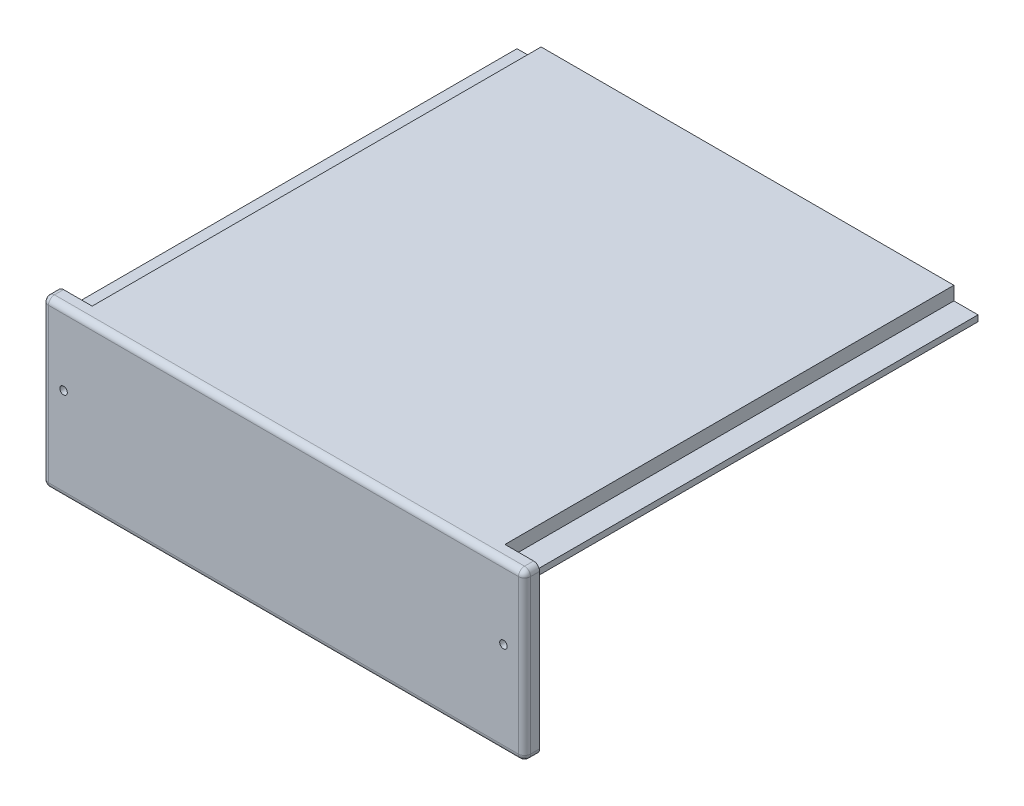
SolidWorks part; units mm, degrees
ref_plane "Front Plane" through (0, 0, 0) normal (0, 0, 1) x (1, 0, 0)
ref_plane "Top Plane" through (0, 0, 0) normal (0, 1, 0) x (1, 0, 0)
ref_plane "Right Plane" through (0, 0, 0) normal (1, 0, 0) x (0, 0, -1)
sketch "Sketch1" plane through (0, 0, 0) normal (0, 0, 1) x (1, 0, 0)
  line L0 (78, 0) -> (-78, 0) construction
  line L1 (80, 55) -> (-80, 55)
  line L2 (80, 55) -> (80, 0)
  line L3 (80, 0) -> (-80, 0)
  line L4 (-80, 55) -> (-80, 0)
  line L5 (-80, 2) -> (-80, 53) construction
  line L6 (-69, 55) -> (69, 55) construction
  line L7 (80, 2) -> (80, 53) construction
extrude "Boss-Extrude1" add sketch "Sketch1" along normal blind 5
sketch "Sketch4" plane through (0, 0, 0) normal (0, 0, -1) x (-1, 0, 0)
  line L1 (-69, 17) -> (69, 17)
  line L2 (-69, 17) -> (-69, 13)
  line L3 (-69, 13) -> (69, 13)
  line L4 (69, 17) -> (69, 13)
  line L5 (-69, 10) -> (69, 10)
  line L6 (-69, 10) -> (-69, 6)
  line L7 (-69, 6) -> (69, 6)
  line L8 (69, 10) -> (69, 6)
  line L12 (77, 10) -> (-77, 10) construction
  line L13 (77, 6) -> (-77, 6) construction
  line L14 (-77, 17) -> (77, 17) construction
  dimension "D1" = 4
extrude "Boss-Extrude3" add sketch "Sketch4" along normal blind 4
fillet "Fillet1" radius 2 8 edges at (80, 27.5, 5) (-80, 27.5, 5) (80, 0, 2.5) (0, 0, 5) (-80, 0, 2.5) (0, 55, 5) (80, 55, 2.5) (-80, 55, 2.5)
sketch "Sketch10" plane through (0, 0, 0) normal (0, 0, -1) x (-1, 0, 0)
  circle A1 centre (-73, 31) radius 1.25
  dimension "D1" = 2.5
extrude "Cut-Extrude1" cut sketch "Sketch10" against normal up to next
mirror "Mirror1" about plane through (0, 0, 0) normal (1, 0, 0) of "Cut-Extrude1"
sketch "Sketch13" plane through (0, 0, 0) normal (0, 0, -1) x (-1, 0, 0)
  line L0 (-68.5, 55) -> (-68.5, 50.5)
  line L1 (-80, 55) -> (80, 55) construction
  line L2 (-69, 55) -> (-69, 51) construction
  line L3 (-68.5, 50.5) -> (-76.5, 50.5)
  line L4 (-76.5, 50.5) -> (-76.5, 48.5)
  line L5 (-76.5, 48.5) -> (-68.5, 48.5)
  line L6 (-68.5, 48.5) -> (-68.5, 45)
  line L7 (-68.5, 45) -> (68.5, 45)
  line L9 (0, 45) -> (0, 55) construction
  line L10 (68.5, 55) -> (-68.5, 55)
  line L12 (76.5, 50.5) -> (76.5, 51) construction
  line L14 (76.5, 48.5) -> (76.5, 48) construction
  line L15 (-77, 51) -> (-77, 48) construction
  line L16 (-76.5, 48.5) -> (-76.5, 48) construction
  line L18 (-76.5, 50.5) -> (-76.5, 51) construction
  line L19 (-69, 51) -> (-77, 51) construction
  line L20 (-69, 45) -> (-68.5, 45) construction
  line L21 (68.5, 48.5) -> (68.5, 45)
  line L22 (76.5, 48.5) -> (68.5, 48.5)
  line L23 (76.5, 50.5) -> (76.5, 48.5)
  line L24 (68.5, 50.5) -> (76.5, 50.5)
  line L25 (68.5, 55) -> (68.5, 50.5)
  line L28 (-69, 48) -> (-77, 48) construction
  dimension "D1" = 2
  dimension "D2" = 0.5
  dimension "D3" = 0.5
extrude "Boss-Extrude4" add sketch "Sketch13" along normal blind 149
